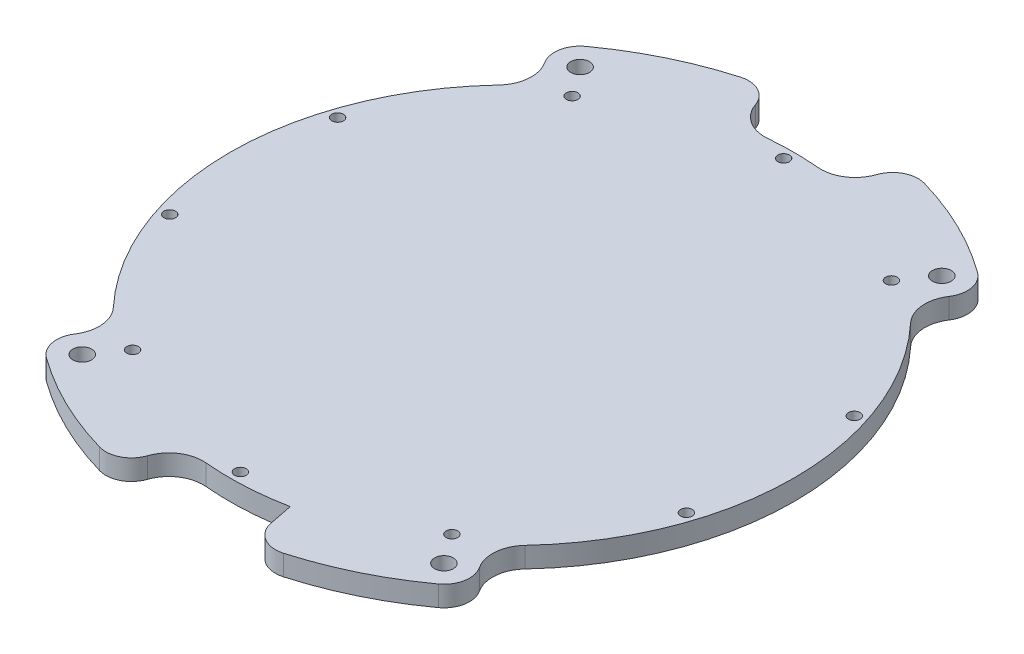
SolidWorks part; units mm, degrees
material "Acrylic (Medium-high impact)"
ref_plane "Front Plane" through (0, 0, 0) normal (0, 0, 1) x (1, 0, 0)
ref_plane "Top Plane" through (0, 0, 0) normal (0, 1, 0) x (1, 0, 0)
ref_plane "Right Plane" through (0, 0, 0) normal (1, 0, 0) x (0, 0, -1)
sketch "Sketch1" plane through (0, 0, 0) normal (0, 1, 0) x (1, 0, 0)
  line L0 (0, 0) -> (0, 79.5) construction
  line L1 (0, 0) -> (46.7289, 64.3169) construction
  line L4 (0, 0) -> (-52.9347, 72.8584) construction
  line L5 (-1000, 0) -> (49000, 0) construction
  line L7 (-58.6141, 67.96) -> (0, 0) construction
  line L9 (-58.6141, -67.96) -> (0, 0) construction
  line L11 (-58.6141, 67.96) -> (-53.9149, 62.5115)
  line L12 (-58.6141, -67.96) -> (-53.9149, -62.5115)
  line L14 (-52.9347, 72.8584) -> (-57.3431, 78.926) construction
  line L15 (0, 0) -> (-26.8906, 93.7786) construction
  line L16 (-42.7666, 87.6844) -> (0, 0) construction
  line L17 (-17.4667, 88.0289) -> (-16.0664, 80.9714)
  line L18 (-17.4667, -88.0289) -> (-16.0664, -80.9714)
  line L19 (17.4667, -88.0289) -> (16.0664, -80.9714)
  line L20 (58.6141, -67.96) -> (53.9149, -62.5115)
  line L21 (58.6141, 67.96) -> (53.9149, 62.5115)
  line L22 (17.4667, 88.0289) -> (16.0664, 80.9714)
  line L23 (0, -1000) -> (0, 49000) construction
  arc A0 (0, 79.5) -> (-51.9229, -60.2019) centre (0, 0) ccw construction
  arc A1 (-53.9149, 62.5115) -> (-53.9149, -62.5115) centre (0, 0) ccw
  arc A4 (-58.6141, 67.96) -> (-57.3431, 78.926) centre (-52.9347, 72.8584) cw
  arc A5 (-58.6141, -67.96) -> (-57.3431, -78.926) centre (-52.9347, -72.8584) ccw
  arc A6 (-16.0664, -80.9714) -> (16.0664, -80.9714) centre (0, 0) ccw
  arc A8 (-57.3431, 78.926) -> (-26.8906, 93.7786) centre (0, 0) cw
  arc A9 (-17.4667, 88.0289) -> (-26.8906, 93.7786) centre (-24.8233, 86.5692) ccw
  arc A10 (-17.4667, -88.0289) -> (-26.8906, -93.7786) centre (-24.8233, -86.5692) cw
  arc A11 (-57.3431, -78.926) -> (-26.8906, -93.7786) centre (0, 0) ccw
  arc A12 (17.4667, -88.0289) -> (26.8906, -93.7786) centre (24.8233, -86.5692) ccw
  arc A13 (57.3431, -78.926) -> (26.8906, -93.7786) centre (0, 0) cw
  arc A14 (58.6141, -67.96) -> (57.3431, -78.926) centre (52.9347, -72.8584) cw
  arc A15 (58.6141, 67.96) -> (57.3431, 78.926) centre (52.9347, 72.8584) ccw
  arc A16 (57.3431, 78.926) -> (26.8906, 93.7786) centre (0, 0) ccw
  arc A17 (17.4667, 88.0289) -> (26.8906, 93.7786) centre (24.8233, 86.5692) cw
  arc A18 (16.0664, 80.9714) -> (-16.0664, 80.9714) centre (0, 0) ccw
  arc A19 (79.5, 0) -> (46.7289, 64.3169) centre (0, 0) ccw construction
  arc A20 (53.9149, -62.5115) -> (53.9149, 62.5115) centre (0, 0) ccw
  circle A21 centre (52.9347, -72.8584) radius 2.75
  circle A22 centre (52.9347, 72.8584) radius 2.75
  circle A23 centre (-52.9347, -72.8584) radius 2.75
  circle A24 centre (-52.9347, 72.8584) radius 2.75
  point P4 (0, 79.5)
  point P5 (46.7289, 64.3169)
  point P8 (75.609, 24.5669)
  point P9 (75.609, -24.5669)
  point P10 (46.7289, -64.3169)
  point P11 (0, -79.5)
  point P12 (-46.7289, -64.3169)
  point P13 (-75.609, -24.5669)
  point P14 (-75.609, 24.5669)
  point P15 (-46.7289, 64.3169)
  point P16 (0, 0)
  dimension "D1" = 159
  dimension "D2" = 165.1
  dimension "D5" = 7.5
  dimension "D6" = 5.5
  dimension "D7" = 20
  dimension "D8" = 97.5579
  dimension "D4" = 36
  dimension "D3" = 10
extrude "Boss-Extrude1" add sketch "Sketch1" along normal mid plane 6
hole_wizard "M3 Clearance Hole1" positions "Sketch2" profile "Sketch3" hole size "M3" standard "ANSI Metric" end condition through all
sketch "Sketch2" plane through (0, 3, 0) normal (0, 1, 0) x (1, 0, 0)
  point P0 (0, 79.5)
  point P3 (46.7289, 64.3169)
  point P6 (75.609, 24.5669)
  point P9 (75.609, -24.5669)
  point P12 (46.7289, -64.3169)
  point P15 (0, -79.5)
  point P18 (-46.7289, -64.3169)
  point P21 (-75.609, -24.5669)
  point P24 (-75.609, 24.5669)
  point P27 (-46.7289, 64.3169)
sketch "Sketch3" plane through (0, 3, -79.5) normal (1, 0, 0) x (0, 0, 1)
  line L0 (0, 0) -> (0, 6)
  line L1 (0, 6) -> (1.7, 6)
  line L2 (1.7, 6) -> (1.7, 0)
  line L5 (1.7, 0) -> (0, 0)
  line L11 (0, -6.35) -> (0, 107.95) construction
  dimension "Thru Hole Dia." = 3.4
  dimension "Thru Hole Depth" = 6
fillet "Fillet2" radius 10 7 edges at (-53.9149, 0, 62.5115) (-53.9149, 0, -62.5115) (-16.0664, 0, 80.9714) (53.9149, 0, 62.5115) (53.9149, 0, -62.5115) (16.0664, 0, -80.9714) (-16.0664, 0, -80.9714)
